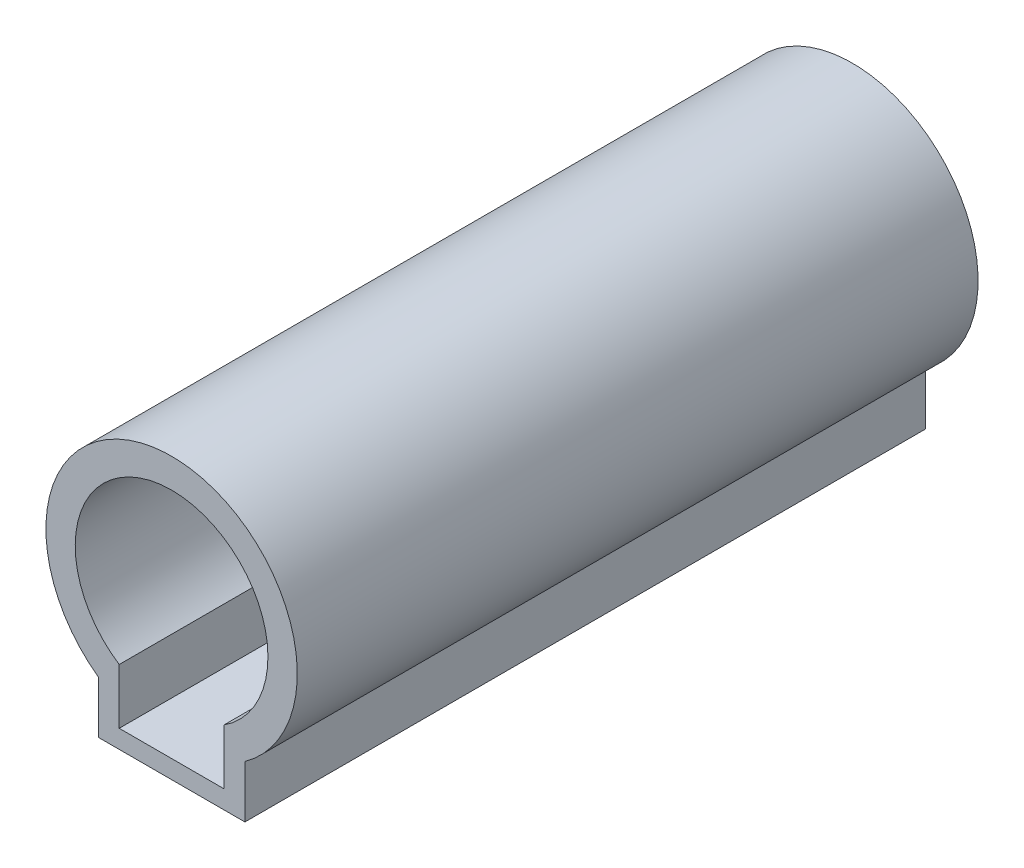
SolidWorks part; units mm, degrees
material "ABS"
ref_plane "Front Plane" through (0, 0, 0) normal (0, 0, 1) x (1, 0, 0)
ref_plane "Top Plane" through (0, 0, 0) normal (0, 1, 0) x (1, 0, 0)
ref_plane "Right Plane" through (0, 0, 0) normal (1, 0, 0) x (0, 0, -1)
sketch "Sketch1" plane through (0, 0, 0) normal (0, 0, 1) x (1, 0, 0)
  line L0 (-7, -14.7468) -> (7, -14.7468)
  line L1 (-7, -14.7468) -> (-7, -9.7468)
  line L2 (7, -14.7468) -> (7, -9.7468)
  circle A0 centre (0, 0) radius 12
  circle A1 centre (0, 0) radius 9.2
  dimension "D1" = 24
  dimension "D2" = 18.4
  dimension "D3" = 14
  dimension "D4" = 5
extrude "Boss-Extrude1" add sketch "Sketch1" along normal blind 65 contours A0 A1 | A0 L1 L0 | A0 L0 L2
sketch "Sketch2" plane through (0, 0, 0) normal (0, 0, 1) x (1, 0, 0)
  line L1 (5, -0.6016) -> (-5, -0.6016)
  line L2 (5, -0.6016) -> (5, -13)
  line L3 (5, -13) -> (-5, -13)
  line L4 (-5, -0.6016) -> (-5, -13)
  line L5 (5, -0.6016) -> (-5, -13) construction
  line L6 (5, -13) -> (-5, -0.6016) construction
  point P0 (0, -6.8008)
  point P5 (0, -13)
  dimension "D1" = 13
  dimension "D2" = 10
extrude "Cut-Extrude3" cut sketch "Sketch2" along normal through all
